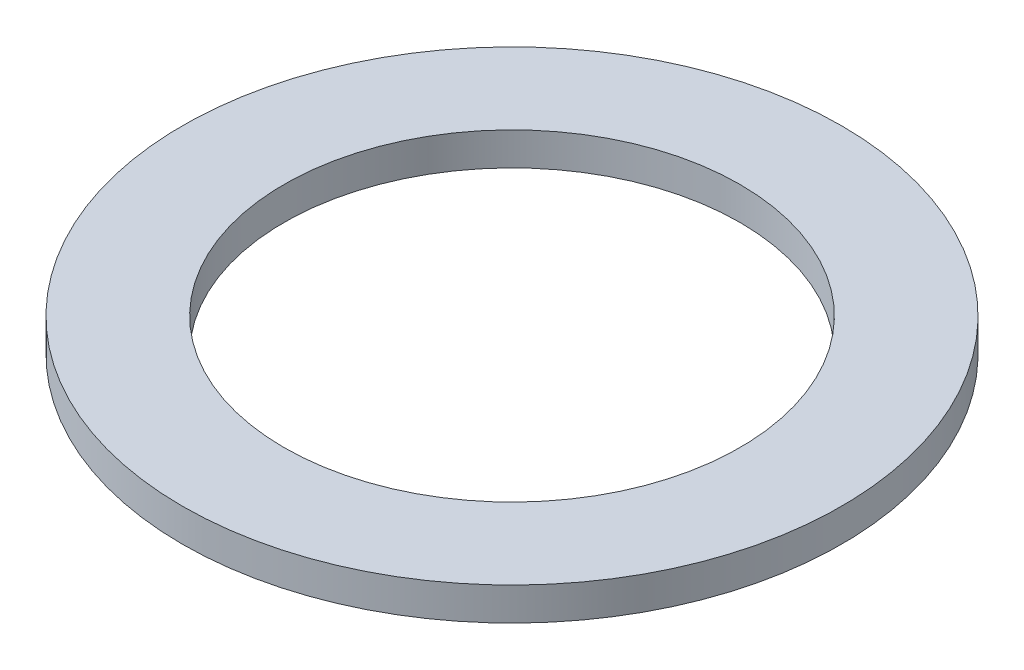
SolidWorks part; units mm, degrees
ref_plane "Front Plane" through (0, 0, 0) normal (0, 0, 1) x (1, 0, 0)
ref_plane "Top Plane" through (0, 0, 0) normal (0, 1, 0) x (1, 0, 0)
ref_plane "Right Plane" through (0, 0, 0) normal (1, 0, 0) x (0, 0, -1)
sketch "Sketch1" plane through (0, 0, 0) normal (0, 1, 0) x (1, 0, 0)
  circle A0 centre (0, 0) radius 30
  circle A1 centre (0, 0) radius 20.75
  dimension "D1" = 41.5
  dimension "D2" = 60
extrude "Boss-Extrude1" add sketch "Sketch1" along normal blind 3
